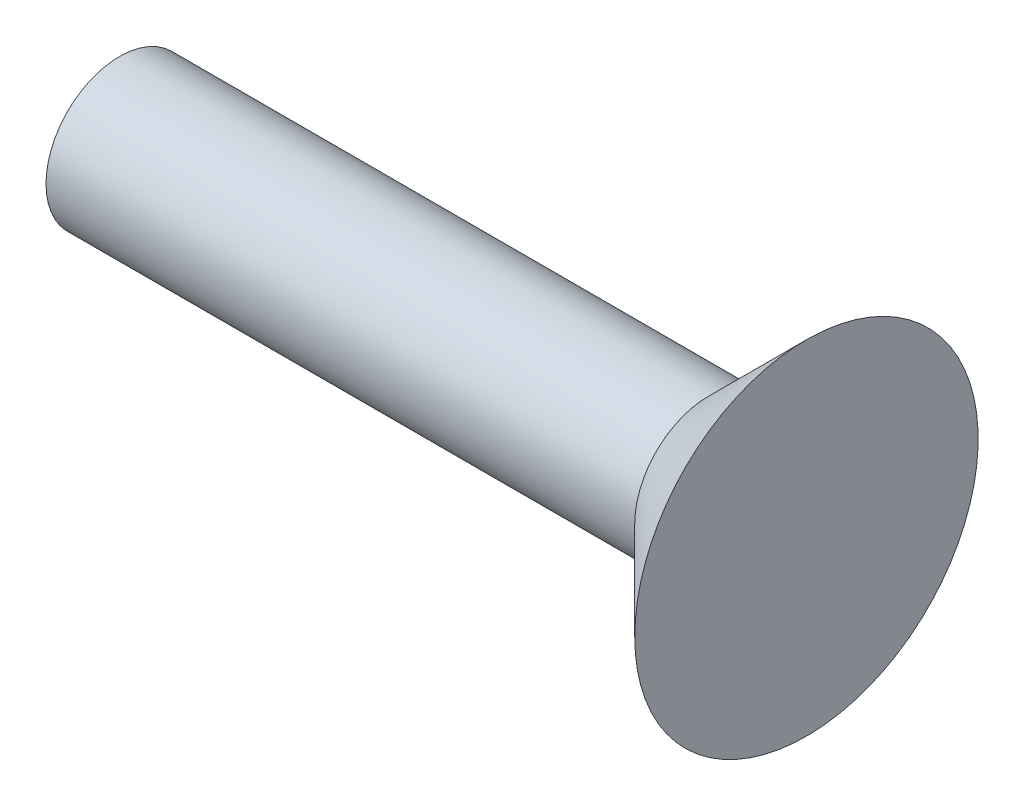
SolidWorks part; units mm, degrees
ref_plane "Front Plane" through (0, 0, 0) normal (0, 0, 1) x (1, 0, 0)
ref_plane "Top Plane" through (0, 0, 0) normal (0, 1, 0) x (1, 0, 0)
ref_plane "Right Plane" through (0, 0, 0) normal (1, 0, 0) x (0, 0, -1)
sketch "Sketch1" plane through (0, 0, 0) normal (0, 0, 1) x (1, 0, 0)
  line L0 (-84.0032, 19.2344) -> (-72.0032, 19.2344)
  line L1 (-70.0032, 17.7344) -> (-70.0032, 21.2344)
  line L2 (-84.0032, 19.2344) -> (-84.0032, 17.7344)
  line L3 (-72.0032, 19.2344) -> (-70.0032, 21.2344)
  line L4 (-84.0032, 17.7344) -> (-70.0032, 17.7344) construction
  line L5 (-70.0032, 17.7344) -> (-84.0032, 17.7344)
revolve "Revolve2" add sketch "Sketch1" angle 360 about L4
